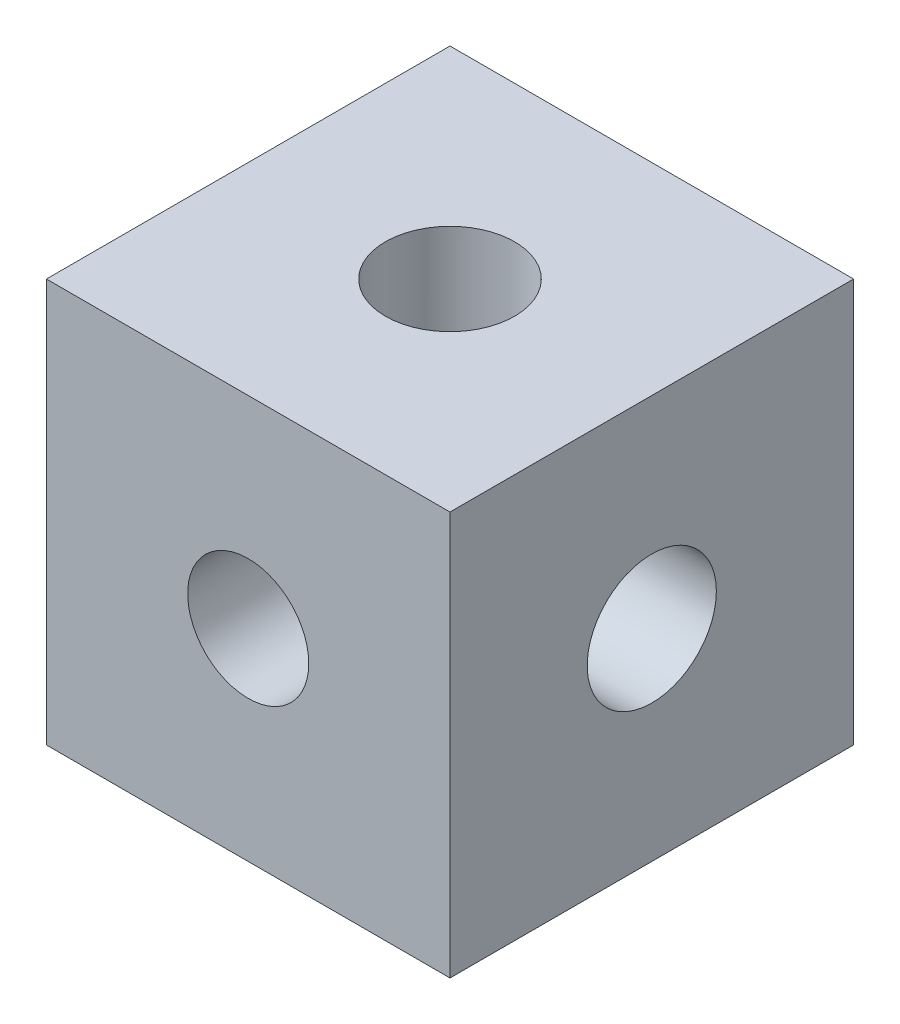
SolidWorks part; units mm, degrees
ref_plane "前视基准面" through (0, 0, 0) normal (0, 0, 1) x (1, 0, 0)
ref_plane "上视基准面" through (0, 0, 0) normal (0, 1, 0) x (1, 0, 0)
ref_plane "右视基准面" through (0, 0, 0) normal (1, 0, 0) x (0, 0, -1)
sketch "草图1" plane through (0, 0, 0) normal (0, 1, 0) x (1, 0, 0)
  line L1 (0, 0) -> (10, 0)
  line L2 (0, 0) -> (0, -10)
  line L3 (0, -10) -> (10, -10)
  line L4 (10, 0) -> (10, -10)
  dimension "D1" = 10
  dimension "D2" = 10
extrude "凸台-拉伸1" add sketch "草图1" along normal blind 10
sketch "草图2" plane through (0, 0, 10) normal (0, 0, 1) x (1, 0, 0)
  line L0 (0, 0) -> (10, 0) construction
  line L1 (10, 10) -> (10, 0) construction
  circle A0 centre (5, 5) radius 1.5
  dimension "D1" = 3
  dimension "D2" = 5
  dimension "D3" = 5
extrude "切除-拉伸1" cut sketch "草图2" against normal blind 10
sketch "草图3" plane through (0, 10, 0) normal (0, 1, 0) x (1, 0, 0)
  line L0 (0, -10) -> (10, -10) construction
  line L1 (0, 0) -> (0, -10) construction
  circle A0 centre (5, -5) radius 1.6
  dimension "D1" = 3.2
  dimension "D2" = 5
  dimension "D3" = 5
extrude "切除-拉伸2" cut sketch "草图3" against normal blind 10
sketch "草图4" plane through (10, 0, 0) normal (1, 0, 0) x (0, 0, -1)
  line L0 (-10, 0) -> (0, 0) construction
  line L1 (0, 10) -> (0, 0) construction
  circle A0 centre (-5, 5) radius 1.6
  dimension "D1" = 3.2
  dimension "D2" = 5
  dimension "D3" = 5
extrude "切除-拉伸3" cut sketch "草图4" against normal blind 10
